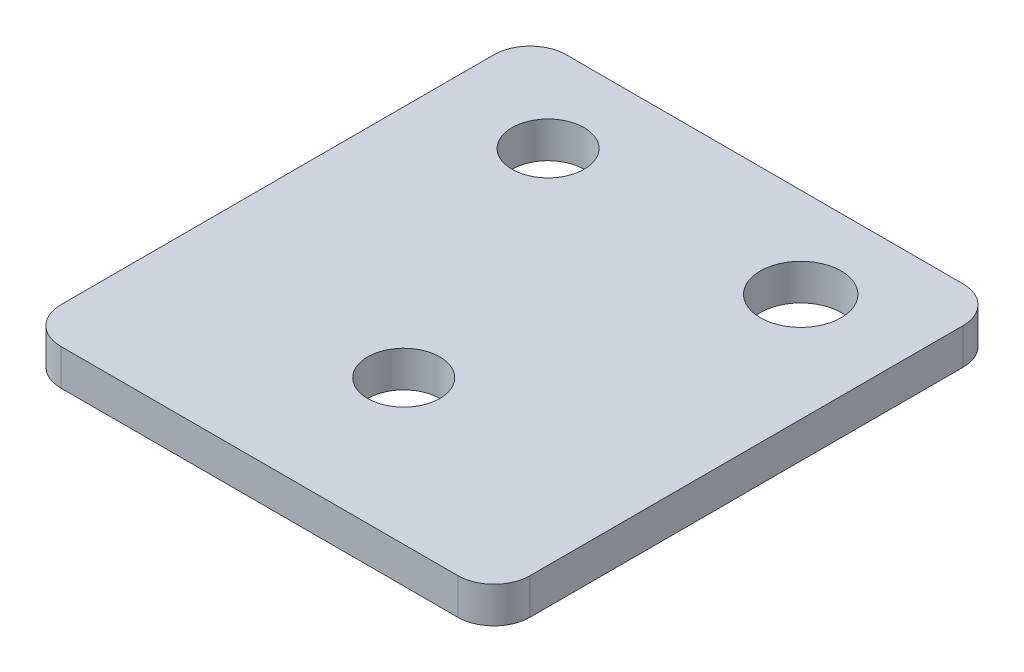
SolidWorks part; units mm, degrees
ref_plane "Front Plane" through (0, 0, 0) normal (0, 0, 1) x (1, 0, 0)
ref_plane "Top Plane" through (0, 0, 0) normal (0, 1, 0) x (1, 0, 0)
ref_plane "Right Plane" through (0, 0, 0) normal (1, 0, 0) x (0, 0, -1)
sketch "Sketch1" plane through (0, 0, 0) normal (0, 1, 0) x (1, 0, 0)
  line L1 (0, 0) -> (41.275, 0)
  line L2 (0, 0) -> (0, 44.45)
  line L3 (0, 44.45) -> (41.275, 44.45)
  line L4 (41.275, 0) -> (41.275, 44.45)
  dimension "D1" = 41.275
  dimension "D2" = 44.45
extrude "Boss-Extrude1" add sketch "Sketch1" along normal blind 3.175
fillet "Fillet1" radius 3.175 4 edges at (41.275, 1.5875, 0) (41.275, 1.5875, -44.45) (0, 1.5875, -44.45) (0, 1.5875, 0)
sketch "Sketch2" plane through (0, 3.175, 0) normal (0, 1, 0) x (1, 0, 0)
  line L0 (20.6375, 44.45) -> (20.6375, 0) construction
  line L1 (38.1, 44.45) -> (3.175, 44.45) construction
  line L2 (3.175, 0) -> (38.1, 0) construction
  line L3 (0, 36.5125) -> (41.275, 36.5125) construction
  line L4 (0, 41.275) -> (0, 3.175) construction
  line L5 (41.275, 3.175) -> (41.275, 41.275) construction
  line L6 (9.525, 44.45) -> (9.525, 0) construction
  line L7 (31.75, 44.45) -> (31.75, 0) construction
  circle A0 centre (9.525, 36.5125) radius 3.175
  circle A1 centre (31.75, 36.5125) radius 3.5617
  circle A2 centre (20.6375, 12.7) radius 3.175
  dimension "D4" = 12.7
  dimension "D1" = 7.9375
  dimension "D2" = 9.525
  dimension "D3" = 9.525
extrude "Cut-Extrude1" cut sketch "Sketch2" against normal through all
